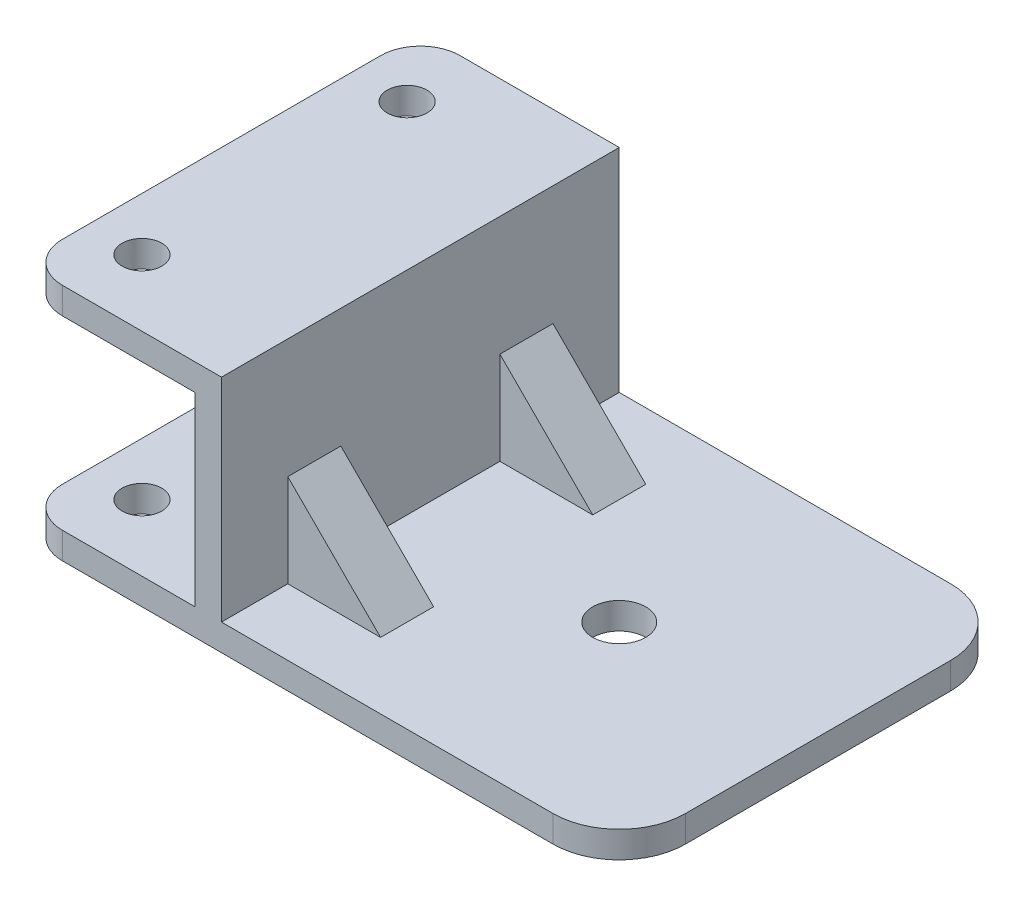
SolidWorks part; units mm, degrees
material "ABS"
ref_plane "Front Plane" through (0, 0, 0) normal (0, 0, 1) x (1, 0, 0)
ref_plane "Top Plane" through (0, 0, 0) normal (0, 1, 0) x (1, 0, 0)
ref_plane "Right Plane" through (0, 0, 0) normal (1, 0, 0) x (0, 0, -1)
sketch "Sketch1" plane through (0, 0, 0) normal (0, 0, 1) x (1, 0, 0)
  line L0 (0, 0) -> (15, 0)
  line L1 (15, 0) -> (15, 18)
  line L2 (15, 18) -> (0, 18)
  line L3 (0, 18) -> (0, 16)
  line L4 (0, 16) -> (13, 16)
  line L5 (13, 16) -> (13, 2)
  line L6 (13, 2) -> (0, 2)
  line L7 (0, 2) -> (0, 0)
  dimension "D1" = 18
  dimension "D2" = 15
  dimension "D3" = 13
  dimension "D4" = 2
  dimension "D5" = 2
extrude "Boss-Extrude1" add sketch "Sketch1" along normal mid plane 30
sketch "Sketch2" plane through (0, 18, 0) normal (0, 1, 0) x (1, 0, 0)
  line L0 (4, 3.7019) -> (4, -33.5199) construction
  line L1 (15, -15) -> (15, 15) construction
  line L2 (15, -15) -> (0, -15) construction
  line L3 (-5.1718, 10) -> (24.0958, 10) construction
  line L4 (-1.9198, -10) -> (25.8696, -10) construction
  circle A0 centre (4, 10) radius 1.5
  circle A1 centre (4, -10) radius 1.5
  point P8 (9.462, 10)
  point P11 (7.5, -15)
  point P12 (4, 10)
  point P13 (4, -10)
  dimension "D4" = 3
  dimension "D5" = 3
  dimension "D1" = 11
  dimension "D2" = 20
  dimension "D3" = 5
extrude "Cut-Extrude1" cut sketch "Sketch2" against normal through all
fillet "Fillet1" radius 3 4 edges at (0, 1, 15) (0, 1, -15) (0, 17, -15) (0, 17, 15)
sketch "Sketch3" plane through (0, 0, 0) normal (0, -1, 0) x (1, 0, 0)
  line L1 (15, -15) -> (45, -15)
  line L2 (15, -15) -> (15, 15)
  line L3 (15, 15) -> (45, 15)
  line L4 (45, -15) -> (45, 15)
  dimension "D1" = 30
  dimension "D2" = 30
extrude "Boss-Extrude2" add sketch "Sketch3" against normal blind 2
sketch "Sketch5" plane through (0, 0, 0) normal (0, 0, 1) x (1, 0, 0)
  line L0 (15, 2) -> (15, 9)
  line L1 (15, 2) -> (15, 18) construction
  line L2 (15, 9) -> (22, 2)
  line L3 (45, 2) -> (15, 2) construction
  line L4 (22, 2) -> (15, 2)
  dimension "D1" = 7
  dimension "D2" = 7
extrude "Boss-Extrude3" add sketch "Sketch5" along normal mid plane 20
sketch "Sketch6" plane through (0, 0, 0) normal (0, 0, 1) x (1, 0, 0)
  line L0 (15, 2) -> (15, 9)
  line L1 (15, 9) -> (22, 2)
  line L2 (22, 2) -> (15, 2)
extrude "Cut-Extrude2" cut sketch "Sketch6" against normal mid plane 12
sketch "Sketch7" plane through (0, 2, 0) normal (0, 1, 0) x (1, 0, 0)
  line L0 (45, 15) -> (45, -15) construction
  line L1 (15, 15) -> (45, 15) construction
  circle A0 centre (30, 0) radius 2
  dimension "D3" = 4
  dimension "D1" = 15
  dimension "D2" = 15
extrude "Cut-Extrude3" cut sketch "Sketch7" against normal blind 12
fillet "Fillet2" radius 5 2 edges at (45, 1, -15) (45, 1, 15)
